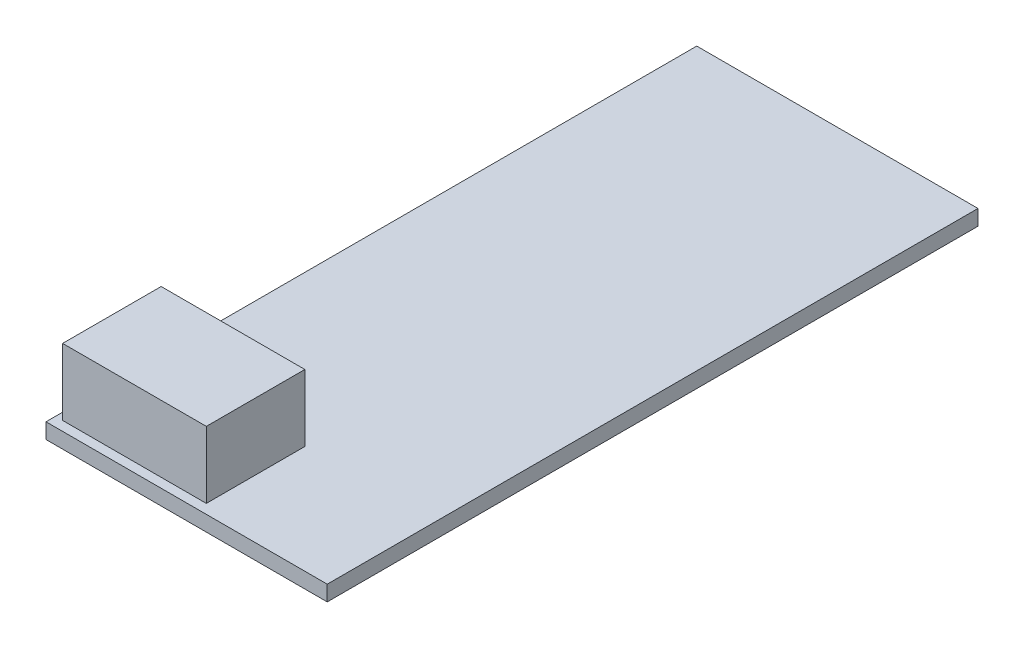
SolidWorks part; units mm, degrees
ref_plane "Front Plane" through (0, 0, 0) normal (0, 0, 1) x (1, 0, 0)
ref_plane "Top Plane" through (0, 0, 0) normal (0, 1, 0) x (1, 0, 0)
ref_plane "Right Plane" through (0, 0, 0) normal (1, 0, 0) x (0, 0, -1)
sketch "Sketch1" plane through (0, 0, 0) normal (0, 1, 0) x (1, 0, 0)
  line L1 (-13.7, -31.7) -> (13.7, -31.7)
  line L2 (-13.7, -31.7) -> (-13.7, 31.7)
  line L3 (-13.7, 31.7) -> (13.7, 31.7)
  line L4 (13.7, -31.7) -> (13.7, 31.7)
  line L5 (-13.7, -31.7) -> (13.7, 31.7) construction
  line L6 (-13.7, 31.7) -> (13.7, -31.7) construction
  point P0 (0, 0)
  dimension "D1" = 27.4
  dimension "D2" = 63.4
extrude "Boss-Extrude1" add sketch "Sketch1" along normal blind 1.5
sketch "Sketch2" plane through (0, 1.5, 0) normal (0, 1, 0) x (1, 0, 0)
  line L1 (-13.0045, -30.7761) -> (0.9955, -30.7761)
  line L2 (-13.0045, -30.7761) -> (-13.0045, -21.1761)
  line L3 (-13.0045, -21.1761) -> (0.9955, -21.1761)
  line L4 (0.9955, -30.7761) -> (0.9955, -21.1761)
  line L5 (-13.0045, -30.7761) -> (0.9955, -21.1761) construction
  line L6 (-13.0045, -21.1761) -> (0.9955, -30.7761) construction
  point P0 (-6.0045, -25.9761)
  dimension "D1" = 14
  dimension "D2" = 9.6
extrude "Boss-Extrude2" add sketch "Sketch2" along normal blind 6.5
